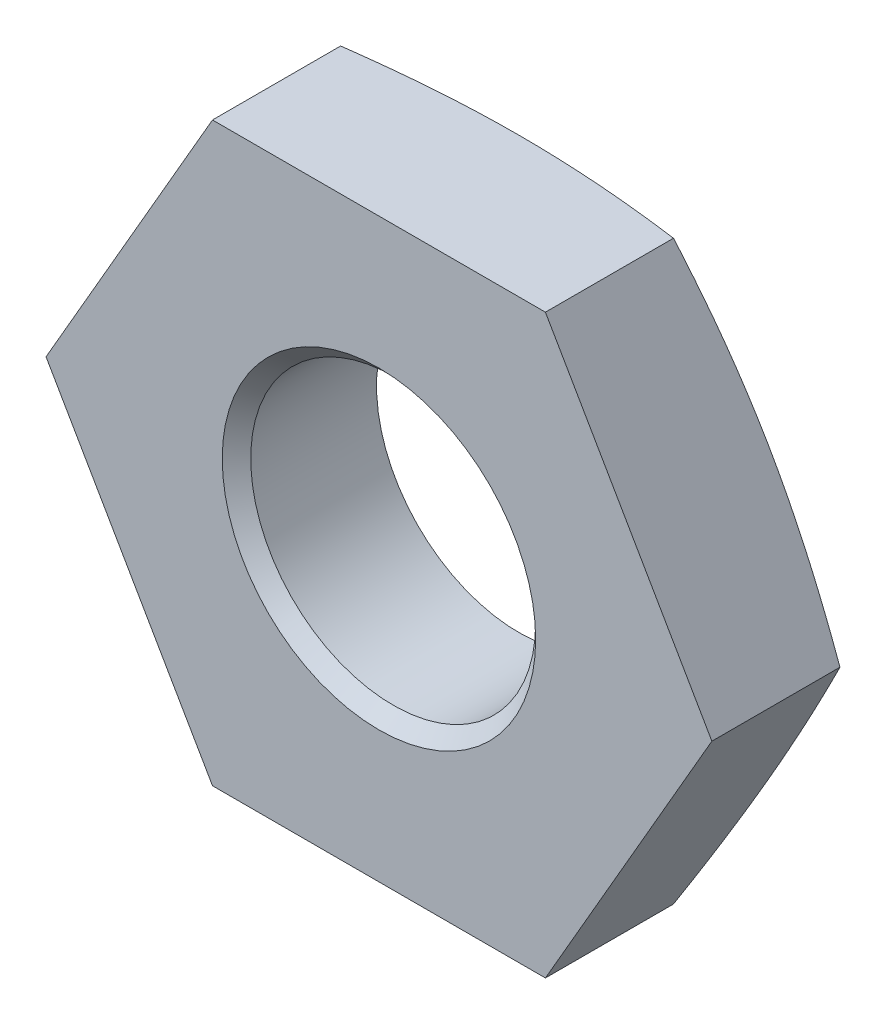
SolidWorks part; units mm, degrees
ref_plane "Front" through (0, 0, 0) normal (0, 0, 1) x (1, 0, 0)
ref_plane "Top" through (0, 0, 0) normal (0, 1, 0) x (1, 0, 0)
ref_plane "Right" through (0, 0, 0) normal (1, 0, 0) x (0, 0, -1)
sketch "Sketch1" plane through (0, 0, 0) normal (0, 0, 1) x (1, 0, 0)
  line L1 (2.0207, -3.5) -> (4.0415, 0)
  line L2 (4.0415, 0) -> (2.0207, 3.5)
  line L3 (2.0207, 3.5) -> (-2.0207, 3.5)
  line L4 (-2.0207, 3.5) -> (-4.0415, 0)
  line L5 (-4.0415, 0) -> (-2.0207, -3.5)
  line L6 (-2.0207, -3.5) -> (2.0207, -3.5)
  circle A0 centre (0, 0) radius 3.5 construction
  circle A1 centre (0, 0) radius 1.7295
  dimension "D" = 3.459
  dimension "s" = 7
  dimension "e" = 8.0829
extrude "BaseNut" add sketch "Sketch1" against normal blind 1.7
cosmetic thread "ThreadCosmetic1" parameters "D2"=4
sketch "Sketch2" plane through (0, 0, 0) normal (0, 1, 0) x (1, 0, 0)
  line L0 (-4.0415, 1.7) -> (-3.5, 1.7)
  line L2 (-3.5, 1.7) -> (-4.0415, 1.5549)
  line L3 (-4.0415, 1.5549) -> (-4.0415, 1.7)
  line L4 (0, 3.3759) -> (0, -9.8171) construction
  line L6 (-9.7712, 0.85) -> (9.8853, 0.85) construction
  dimension "dw" = 7
  dimension "Angle" = 15
  dimension "D2" = 0.85
revolve "Double-Chamfer" cut sketch "Sketch2" angle 360 about L4
chamfer "Chamfer1" distance 0.1729 angle 45 1 edges at (1.7295, 0, 0)
sketch "Sketch3" plane through (0, 0, 0) normal (0, 1, 0) x (1, 0, 0)
  line L0 (0, 2.7394) -> (0, -0.894) construction
  line L1 (1.459, 0.3082) -> (1.7295, 0.3082)
  line L2 (1.7295, 0.3082) -> (1.9638, 0.1729)
  line L3 (1.9638, 0.1729) -> (1.7295, 0.0377)
  line L4 (1.7295, 0.0377) -> (1.459, 0.0377)
  line L5 (1.459, 0.0377) -> (1.459, 0.3082)
  line L6 (1.7295, 0.1729) -> (-1.7295, 0.1729) construction
  dimension "D1" = 0.2705
  dimension "D2" = 3.459
revolve "Cut-Revolve10" [suppressed] cut sketch "Sketch3" angle 360 about L0
pattern_linear "LPattern10" [suppressed] count 5 spacing 0.3246 along (0, 0, 1)
equation "\"dw@Sketch2\" = \"s@Sketch1\""
equation "\"D2@Sketch2\" = \"m@BaseNut\" / 2"
equation "\"D1@Chamfer1\" = \"D@Sketch1\" / 20"
equation "\"D2@Sketch3\" = \"D@Sketch1\""
equation "\"D1@Sketch3\" = (  \"D2@ThreadCosmetic1\" - \"D@Sketch1\" )  / 2"
equation "\"D3@LPattern10\" = \"D1@Sketch3\" * 1.2"
equation "\"D1@LPattern10\" = (  \"m@BaseNut\"  - \"D1@Chamfer1\")  / \"D3@LPattern10\""
